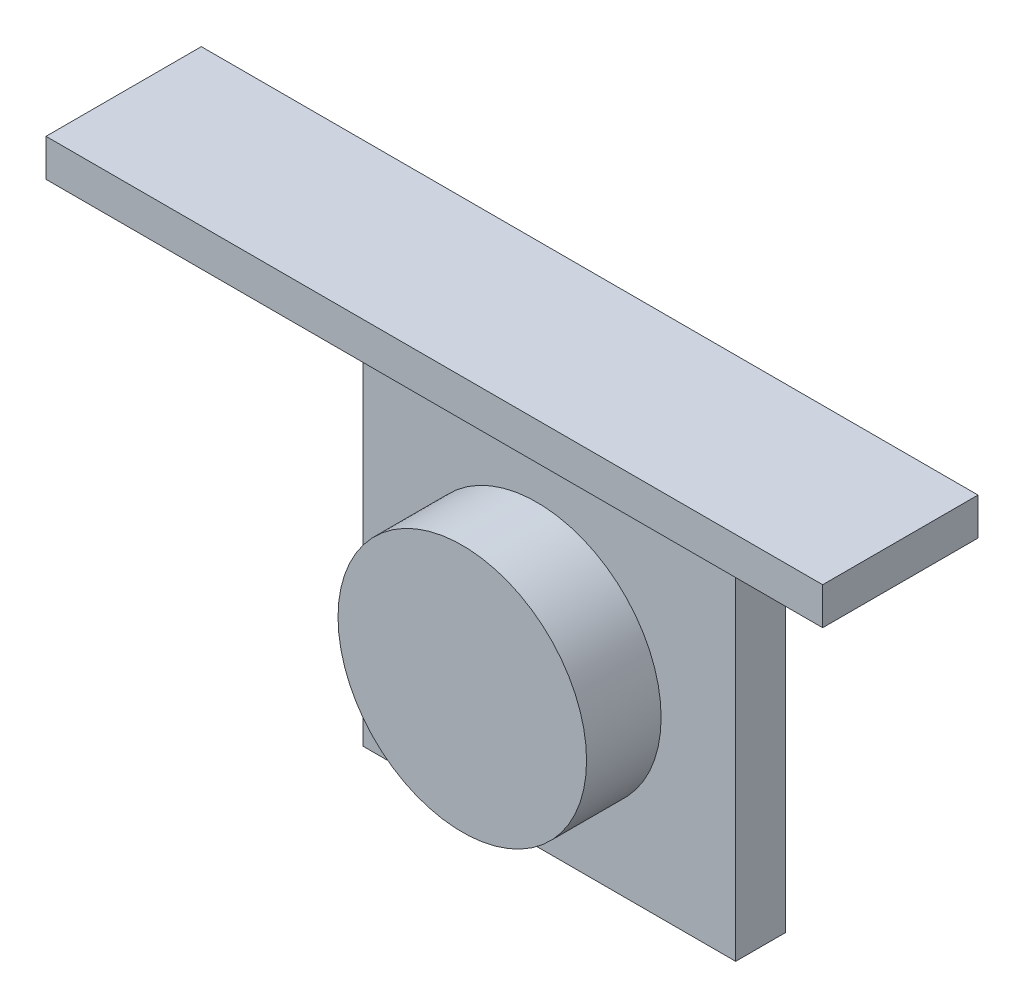
SolidWorks part; units mm, degrees
ref_plane "前视基准面" through (0, 0, 0) normal (0, 0, 1) x (1, 0, 0)
ref_plane "上视基准面" through (0, 0, 0) normal (0, 1, 0) x (1, 0, 0)
ref_plane "右视基准面" through (0, 0, 0) normal (1, 0, 0) x (0, 0, -1)
other "Configuration Table"
sketch "草图1" plane through (0, 0, 0) normal (0, 0, 1) x (1, 0, 0)
  line L1 (-6, -6) -> (6, -6)
  line L2 (-6, -6) -> (-6, 6)
  line L3 (-6, 6) -> (6, 6)
  line L4 (6, -6) -> (6, 6)
  line L5 (-6, -6) -> (6, 6) construction
  line L6 (-6, 6) -> (6, -6) construction
  point P0 (0, 0)
extrude "WS2812 RGB LED board - 12 x 12 mm" add sketch "草图1" along normal blind 1.6 from offset 0.8 separate body
sketch "草图2" plane through (0, 0, 0) normal (0, 0, 1) x (1, 0, 0)
  circle A0 centre (0, 0) radius 4
extrude "RGB LED diffuser" add sketch "草图2" along normal blind 2.4 from offset 1.2 separate body
sketch "草图3" plane through (0, 0, 0) normal (0, 0, 1) x (1, 0, 0)
  line L1 (-12.5, 8.4) -> (12.5, 8.4)
  line L2 (-12.5, 8.4) -> (-12.5, 9.6)
  line L3 (-12.5, 9.6) -> (12.5, 9.6)
  line L4 (12.5, 8.4) -> (12.5, 9.6)
  line L5 (-12.5, 8.4) -> (12.5, 9.6) construction
  line L6 (-12.5, 9.6) -> (12.5, 8.4) construction
  point P0 (0, 9)
extrude "led label plate - WS2812" add sketch "草图3" along normal blind 5 from offset 0.5 separate body
